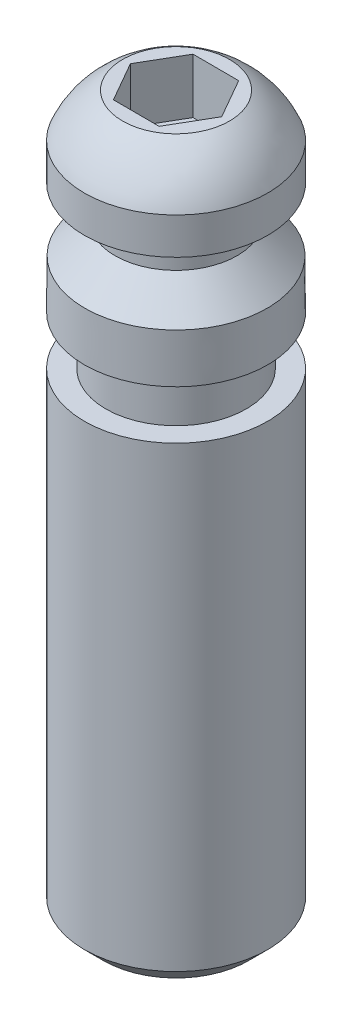
SolidWorks part; units mm, degrees
ref_plane "Front Plane" through (0, 0, 0) normal (0, 0, 1) x (1, 0, 0)
ref_plane "Top Plane" through (0, 0, 0) normal (0, 1, 0) x (1, 0, 0)
ref_plane "Right Plane" through (0, 0, 0) normal (1, 0, 0) x (0, 0, -1)
sketch "Sketch1" plane through (0, 0, 0) normal (0, 1, 0) x (1, 0, 0)
  circle A0 centre (0, 0) radius 3
  dimension "D1" = 6
extrude "Boss-Extrude1" add sketch "Sketch1" along normal blind 23.5
sketch "Sketch2" plane through (0, 0, 0) normal (0, 0, 1) x (1, 0, 0)
  line L0 (0, 23.5) -> (1.75, 23.5) construction
  line L1 (3, 23.5) -> (-3, 23.5) construction
  line L2 (3, 0) -> (3, 23.5) construction
  line L3 (3, 22.0816) -> (3, 20.8816)
  line L4 (3, 20.8816) -> (0, 20.8816) construction
  line L5 (3, 20.8816) -> (1.9954, 20.3015)
  line L6 (0, 20.8816) -> (1.998, 20.8816) construction
  line L7 (1.9954, 20.3015) -> (1.9954, 19.8015)
  line L8 (1.9954, 19.8015) -> (3, 19.8015) construction
  line L9 (1.9954, 19.8015) -> (2.9868, 18.8101)
  line L10 (2.9868, 18.8101) -> (3, 17.2101)
  line L11 (3, 17.2101) -> (2.3, 17.2101)
  line L12 (2.3, 17.2101) -> (2.3, 15.6101)
  line L13 (2.3, 15.6101) -> (3, 15.6101)
  line L14 (3, 15.6101) -> (5.1422, 15.6101)
  line L15 (5.1422, 15.6101) -> (5.1422, 23.5)
  line L16 (5.1422, 23.5) -> (1.75, 23.5)
  arc A0 (1.75, 23.5) -> (3, 22.0816) centre (0.3205, 20.9803) cw
  dimension "D1" = 1.75
  dimension "D2" = 1.2
  dimension "D3" = 30
  dimension "D4" = 1.998
  dimension "D5" = 0.5
  dimension "D6" = 45
  dimension "D7" = 1.6
  dimension "D8" = 0.7
  dimension "D9" = 1.6
ref_axis "Axis1" through (0, 23.5, 0) along (0, -1, 0)
revolve "Cut-Revolve1" cut sketch "Sketch2" angle 360 about axis through (0, 23.5, 0) along (0, -1, 0)
chamfer "Chamfer1" distance 0.625 angle 45 1 edges at (0, 0, 3)
sketch "Sketch3" plane through (0, 23.5, 0) normal (0, 1, 0) x (1, 0, 0)
  line L1 (0.746, -1.3013) -> (1.5, -0.0046)
  line L2 (1.5, -0.0046) -> (0.754, 1.2967)
  line L3 (0.754, 1.2967) -> (-0.746, 1.3013)
  line L4 (-0.746, 1.3013) -> (-1.5, 0.0046)
  line L5 (-1.5, 0.0046) -> (-0.754, -1.2967)
  line L6 (-0.754, -1.2967) -> (0.746, -1.3013)
  circle A0 centre (0, 0) radius 1.299 construction
extrude "Cut-Extrude1" cut sketch "Sketch3" against normal blind 1.8
